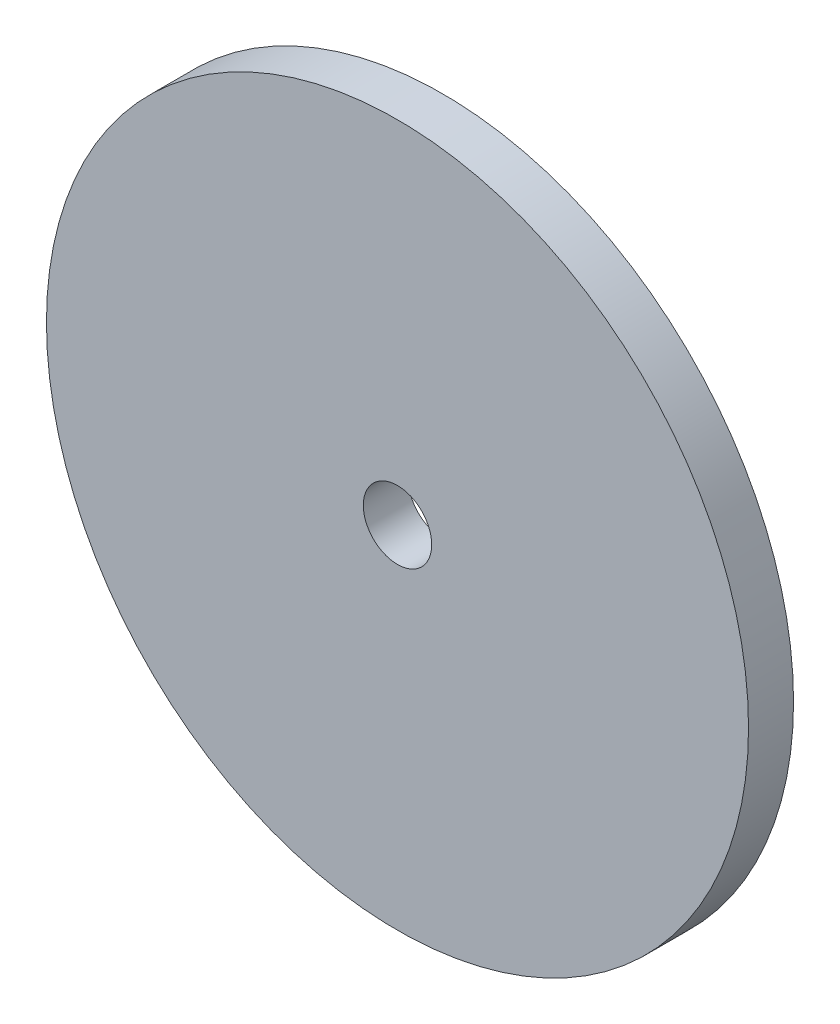
SolidWorks part; units mm, degrees
material "CARBONITE"
ref_plane "Front Plane" through (0, 0, 0) normal (0, 0, 1) x (1, 0, 0)
ref_plane "Top Plane" through (0, 0, 0) normal (0, 1, 0) x (1, 0, 0)
ref_plane "Right Plane" through (0, 0, 0) normal (1, 0, 0) x (0, 0, -1)
sketch "Sketch1" plane through (0, 0, 0) normal (0, 0, 1) x (1, 0, 0)
  circle A0 centre (0, 0) radius 49.53
  dimension "D1" = 99.06
extrude "Boss-Extrude1" add sketch "Sketch1" along normal blind 6.35
sketch "Sketch2" plane through (0, 0, 0) normal (0, 0, -1) x (-1, 0, 0)
  circle A0 centre (0, 0) radius 4.826
  dimension "D1" = 9.652
extrude "Cut-Extrude1" cut sketch "Sketch2" against normal blind 6.35
